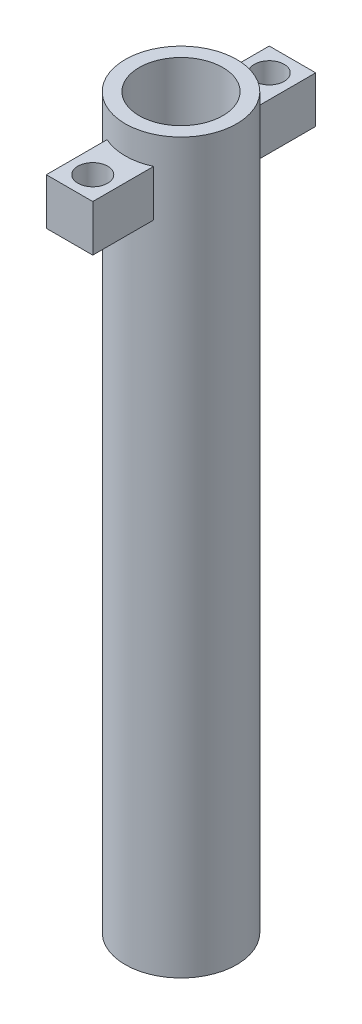
SolidWorks part; units mm, degrees
ref_plane "Front Plane" through (0, 0, 0) normal (0, 0, 1) x (1, 0, 0)
ref_plane "Top Plane" through (0, 0, 0) normal (0, 1, 0) x (1, 0, 0)
ref_plane "Right Plane" through (0, 0, 0) normal (1, 0, 0) x (0, 0, -1)
sketch "Sketch1" plane through (0, 0, 0) normal (0, 1, 0) x (1, 0, 0)
  circle A0 centre (0, 0) radius 6
  circle A1 centre (0, 0) radius 4.5
  dimension "D1" = 9
  dimension "D2" = 12
extrude "Boss-Extrude1" add sketch "Sketch1" along normal blind 78.4
sketch "Sketch2" plane through (0, 78.4, 0) normal (0, 1, 0) x (1, 0, 0)
  line L0 (0, 0) -> (0, 9.5) construction
  line L1 (0, 0) -> (0, -9.5) construction
  line L3 (-2.5, 12) -> (2.5, 12)
  line L4 (-2.5, 12) -> (-2.5, 5.4544)
  line L6 (2.5, 12) -> (2.5, 5.4544)
  line L8 (-2.5, -5.4544) -> (-2.5, -12)
  line L9 (-2.5, -12) -> (2.5, -12)
  line L10 (2.5, -5.4544) -> (2.5, -12)
  arc A0 (-2.5, 5.4544) -> (-2.5, -5.4544) centre (0, 0) ccw
  circle A1 centre (0, 9.5) radius 1.6
  circle A2 centre (0, -9.5) radius 1.6
  arc A3 (2.5, -5.4544) -> (2.5, 5.4544) centre (0, 0) ccw
  circle A4 centre (0, 0) radius 4.5
  dimension "D7" = 3.2
  dimension "D1" = 9.5
  dimension "D2" = 2.5
  dimension "D4" = 2.5
  dimension "D5" = 2.5
  dimension "D6" = 2.5
extrude "Boss-Extrude2" add sketch "Sketch2" against normal blind 8
sketch "Sketch3" plane through (0, 78.4, 0) normal (0, 1, 0) x (1, 0, 0)
  circle A0 centre (0, 0) radius 6
extrude "Cut-Extrude1" cut sketch "Sketch3" against normal blind 3 flip side to cut
